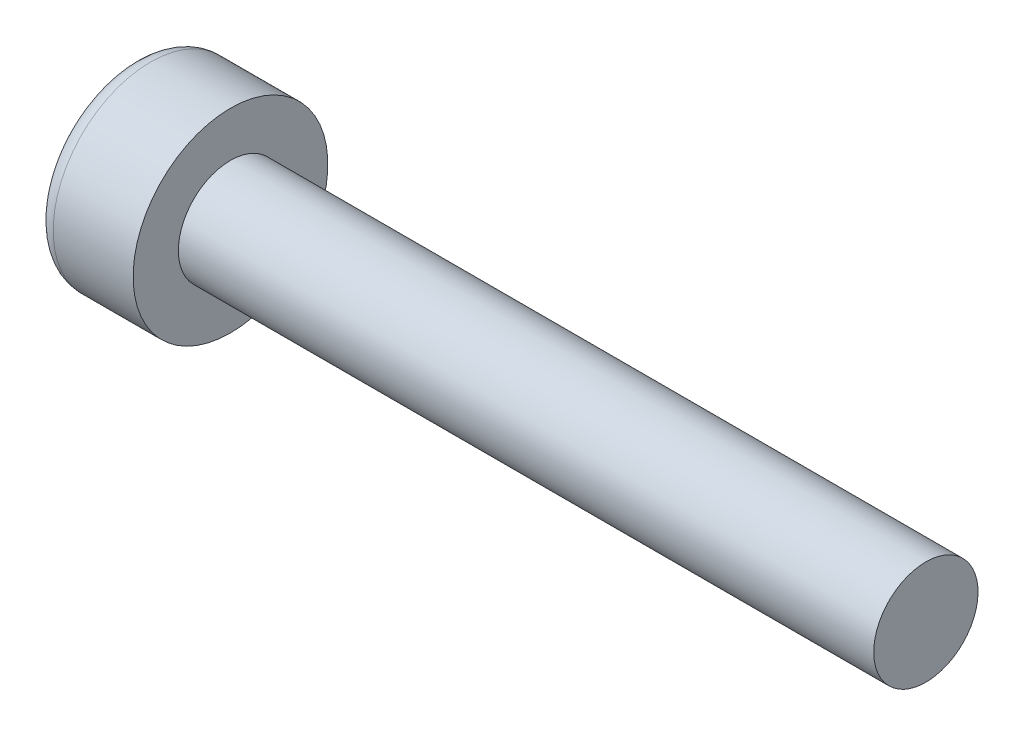
SolidWorks part; units mm, degrees
ref_plane "Front Plane" through (0, 0, 0) normal (0, 0, 1) x (1, 0, 0)
ref_plane "Top Plane" through (0, 0, 0) normal (0, 1, 0) x (1, 0, 0)
ref_plane "Right Plane" through (0, 0, 0) normal (1, 0, 0) x (0, 0, -1)
sketch "Sketch1" plane through (0, 0, 0) normal (0, 0, 1) x (1, 0, 0)
  line L0 (0, 0) -> (20, 0)
  line L1 (20, 0) -> (20, -1.5)
  line L2 (20, -1.5) -> (-2.8, -1.5)
  line L3 (-2.8, -1.5) -> (-2.8, 0.8)
  line L4 (-2.3, 1.3) -> (0, 1.3)
  line L5 (0, 1.3) -> (0, 0)
  arc A0 (-2.8, 0.8) -> (-2.3, 1.3) centre (-2.3, 0.8) cw
  point P9 (-2.8, 1.3)
  dimension "D4" = 0.5
  dimension "D1" = 1.5
  dimension "D2" = 2.8
  dimension "D3" = 2.8
  dimension "D5" = 20
revolve "Revolve1" add sketch "Sketch1" angle 360 about L2
cosmetic thread "Cosmetic Thread1"
